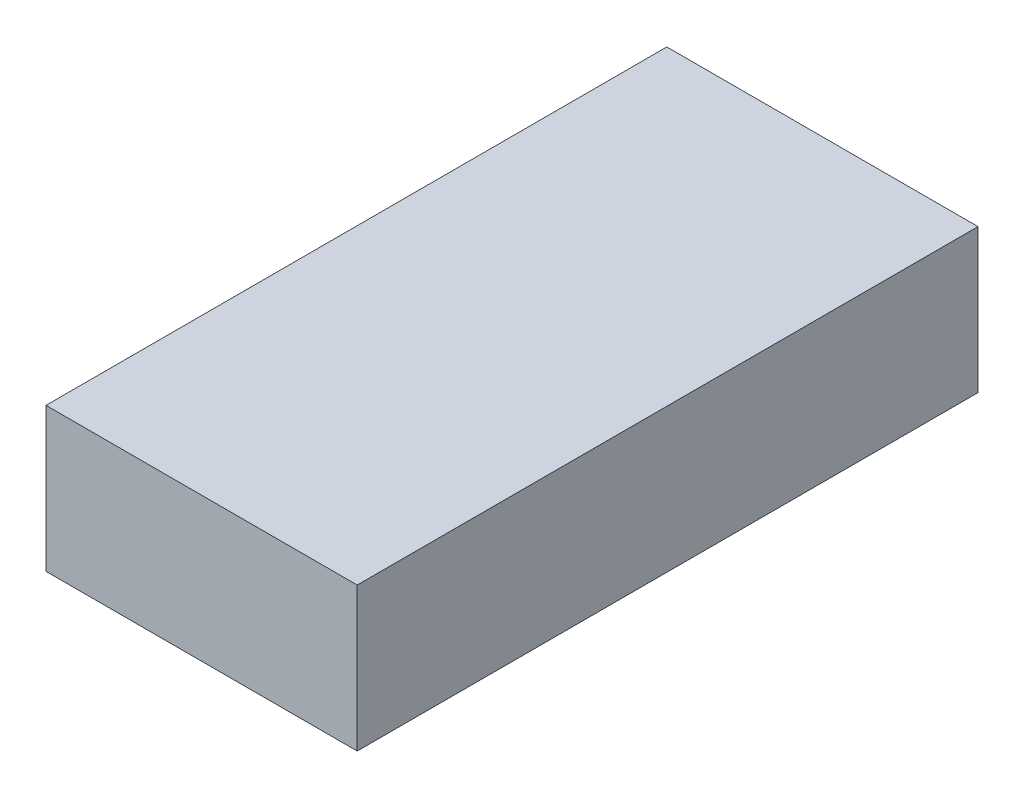
SolidWorks part; units mm, degrees
ref_plane "前视基准面" through (0, 0, 0) normal (0, 0, 1) x (1, 0, 0)
ref_plane "上视基准面" through (0, 0, 0) normal (0, 1, 0) x (1, 0, 0)
ref_plane "右视基准面" through (0, 0, 0) normal (1, 0, 0) x (0, 0, -1)
other "Configuration Table"
sketch "草图1" plane through (0, 0, 0) normal (0, 0, 1) x (1, 0, 0)
  line L1 (-75.1928, -34.7425) -> (75.1928, -34.7425)
  line L2 (-75.1928, -34.7425) -> (-75.1928, 34.7425)
  line L3 (-75.1928, 34.7425) -> (75.1928, 34.7425)
  line L4 (75.1928, -34.7425) -> (75.1928, 34.7425)
  line L5 (-75.1928, -34.7425) -> (75.1928, 34.7425) construction
  line L6 (-75.1928, 34.7425) -> (75.1928, -34.7425) construction
  point P0 (0, 0)
extrude "凸台-拉伸1" add sketch "草图1" along normal blind 300
